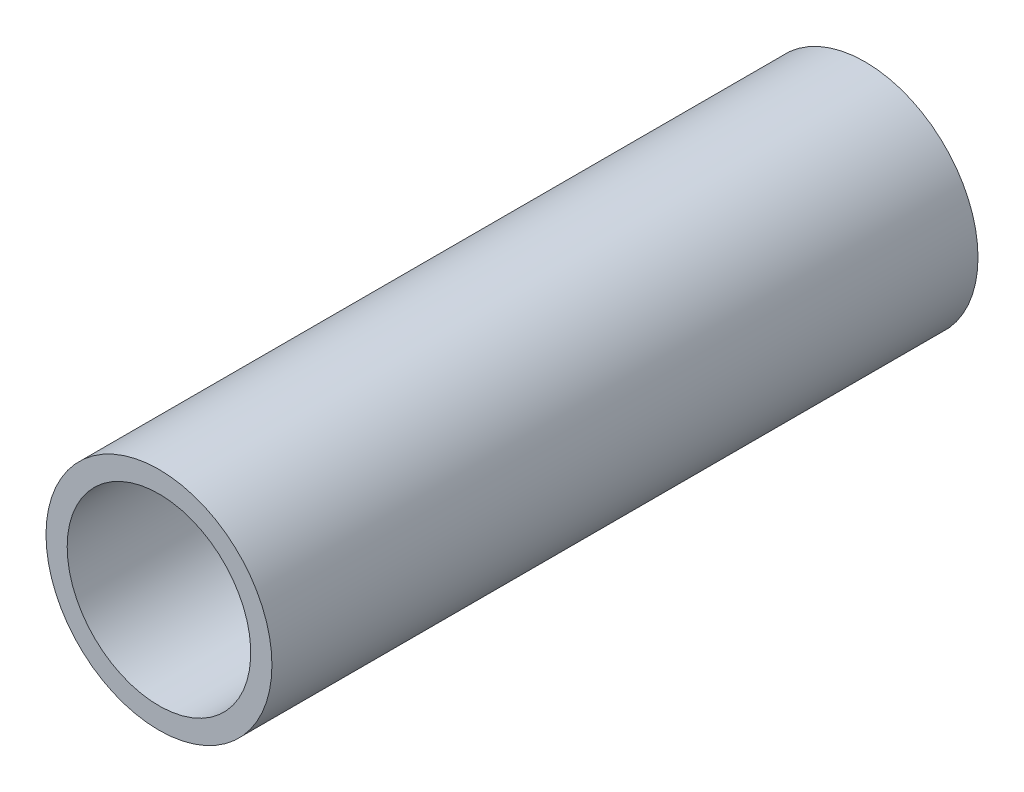
SolidWorks part; units mm, degrees
ref_plane "Alzado" through (0, 0, 0) normal (0, 0, 1) x (1, 0, 0)
ref_plane "Planta" through (0, 0, 0) normal (0, 1, 0) x (1, 0, 0)
ref_plane "Vista lateral" through (0, 0, 0) normal (1, 0, 0) x (0, 0, -1)
sketch "Croquis1" plane through (0, 0, 0) normal (0, 0, 1) x (1, 0, 0)
  circle A0 centre (0, 0) radius 16
  dimension "D1" = 32
extrude "Extruir1" add sketch "Croquis1" along normal mid plane 100
shell "Vaciado1" thickness 3
